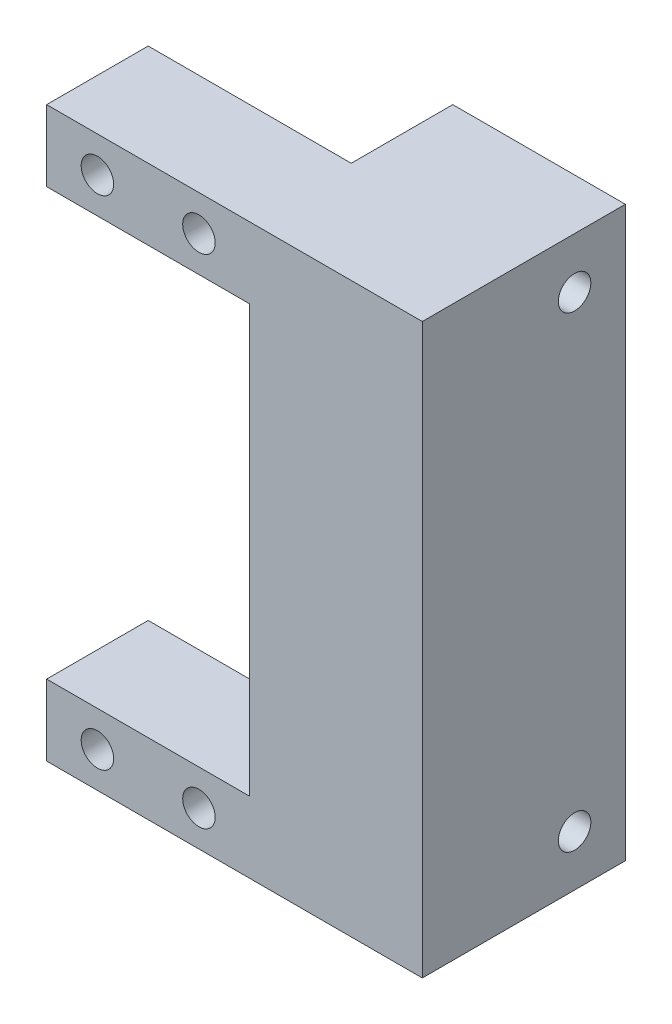
SolidWorks part; units mm, degrees
ref_plane "正面" through (0, 0, 0) normal (0, 0, 1) x (1, 0, 0)
ref_plane "平面" through (0, 0, 0) normal (0, 1, 0) x (1, 0, 0)
ref_plane "右側面" through (0, 0, 0) normal (1, 0, 0) x (0, 0, -1)
sketch "ｽｹｯﾁ1" plane through (0, 0, 0) normal (0, 0, 1) x (1, 0, 0)
  line L0 (-60.9286, 23.8571) -> (-60.9286, 16.8571)
  line L1 (-60.9286, 16.8571) -> (-40.9286, 16.8571)
  line L2 (-40.9286, 16.8571) -> (-40.9286, -25.1429)
  line L3 (-40.9286, -25.1429) -> (-60.9286, -25.1429)
  line L4 (-60.9286, -25.1429) -> (-60.9286, -32.1429)
  line L5 (-60.9286, -32.1429) -> (-33.9286, -32.1429)
  line L6 (-33.9286, -32.1429) -> (-33.9286, 23.8571)
  line L7 (-33.9286, 23.8571) -> (-60.9286, 23.8571)
  dimension "D1" = 42
  dimension "D2" = 56
  dimension "D3" = 20
  dimension "D4" = 20
  dimension "D5" = 7
  dimension "D6" = 7
extrude "ﾎﾞｽ - 押し出し1" add sketch "ｽｹｯﾁ1" along normal blind 10
sketch "ｽｹｯﾁ2" plane through (0, 0, 0) normal (0, 0, -1) x (-1, 0, 0)
  line L0 (60.9286, 16.8571) -> (40.9286, 16.8571) construction
  line L1 (40.9286, 16.8571) -> (40.9286, -25.1429) construction
  circle A0 centre (45.9286, 20.3571) radius 1.6
  circle A1 centre (55.9286, 20.3571) radius 1.6
  circle A2 centre (45.9286, -28.6429) radius 1.6
  circle A3 centre (55.9286, -28.6429) radius 1.6
  dimension "D1" = 3.2
  dimension "D2" = 3.2
  dimension "D3" = 10
  dimension "D4" = 3.2
  dimension "D5" = 3.2
  dimension "D6" = 10
  dimension "D7" = 49
  dimension "D8" = 49
  dimension "D9" = 3.5
  dimension "D10" = 3.5
  dimension "D11" = 5
  dimension "D12" = 5
extrude "ｶｯﾄ - 押し出し1" cut sketch "ｽｹｯﾁ2" against normal blind 10
sketch "ｽｹｯﾁ3" plane through (0, 0, 0) normal (0, 0, -1) x (-1, 0, 0)
  line L0 (60.9286, -32.1429) -> (33.9286, -32.1429) construction
  line L5 (33.9286, 23.8571) -> (40.9286, 23.8571)
  line L6 (33.9286, 23.8571) -> (33.9286, -32.1429)
  line L7 (33.9286, -32.1429) -> (40.9286, -32.1429)
  line L8 (40.9286, 23.8571) -> (40.9286, -32.1429)
  dimension "D1" = 7
extrude "ﾎﾞｽ - 押し出し2" add sketch "ｽｹｯﾁ3" along normal blind 10
sketch "ｽｹｯﾁ4" plane through (-40.9286, 0, 0) normal (-1, 0, 0) x (0, 0, 1)
  line L0 (-5, 23.8571) -> (-5, -32.1429) construction
  line L1 (-10, 23.8571) -> (0, 23.8571) construction
  line L2 (-10, -32.1429) -> (0, -32.1429) construction
  line L3 (-10, -32.1429) -> (-10, 23.8571) construction
  circle A0 centre (-5, 18.8571) radius 1.6
  circle A1 centre (-5, -27.1429) radius 1.6
  dimension "D2" = 3.2
  dimension "D3" = 3.2
  dimension "D4" = 5
  dimension "D5" = 5
  dimension "D1" = 5
extrude "ｶｯﾄ - 押し出し2" cut sketch "ｽｹｯﾁ4" against normal through all both and the other way through all
sketch "ｽｹｯﾁ5" plane through (-33.9286, 0, 0) normal (1, 0, 0) x (0, 0, -1)
  line L0 (-10, 23.8571) -> (-10, -32.1429)
  line L1 (-10, -32.1429) -> (10, -32.1429)
  line L2 (10, -32.1429) -> (10, 23.8571)
  line L3 (10, 23.8571) -> (-10, 23.8571)
extrude "ﾎﾞｽ - 押し出し3" add sketch "ｽｹｯﾁ5" along normal blind 10
sketch "ｽｹｯﾁ6" plane through (-40.9286, 0, 0) normal (-1, 0, 0) x (0, 0, 1)
  circle A0 centre (-5, 18.8571) radius 1.6
  circle A1 centre (-5, -27.1429) radius 1.6
extrude "ｶｯﾄ - 押し出し3" cut sketch "ｽｹｯﾁ6" against normal through all
